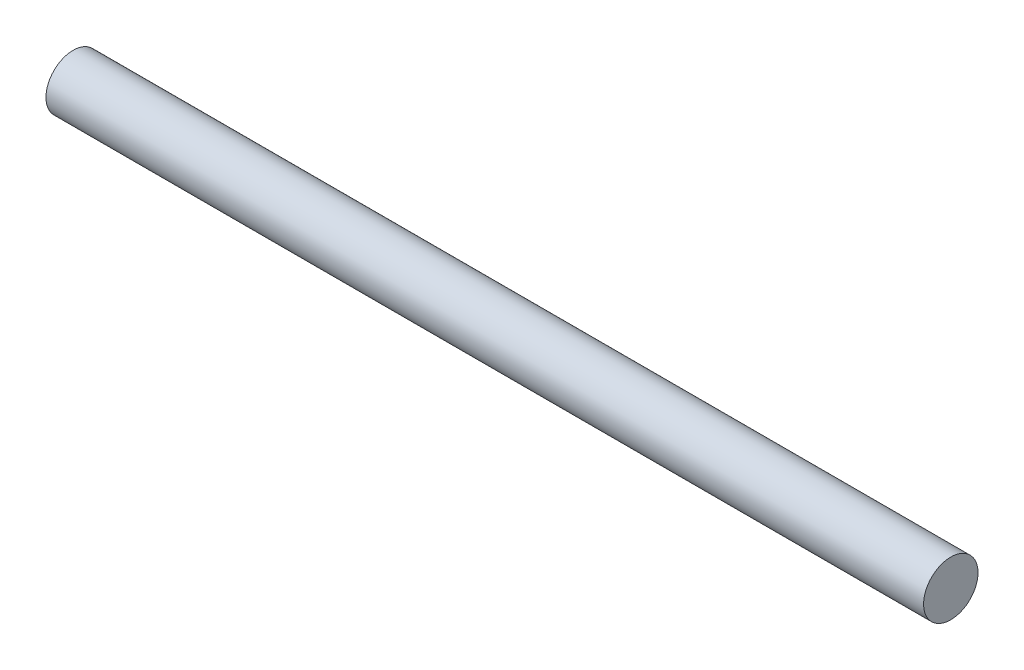
SolidWorks part; units mm, degrees
ref_plane "前视基准面" through (0, 0, 0) normal (0, 0, 1) x (1, 0, 0)
ref_plane "上视基准面" through (0, 0, 0) normal (0, 1, 0) x (1, 0, 0)
ref_plane "右视基准面" through (0, 0, 0) normal (1, 0, 0) x (0, 0, -1)
sketch "草图1" plane through (0, 0, 0) normal (1, 0, 0) x (0, 0, -1)
  circle A0 centre (0, 0) radius 4
  dimension "D1" = 8
extrude "凸台-拉伸1" add sketch "草图1" along normal blind 129
